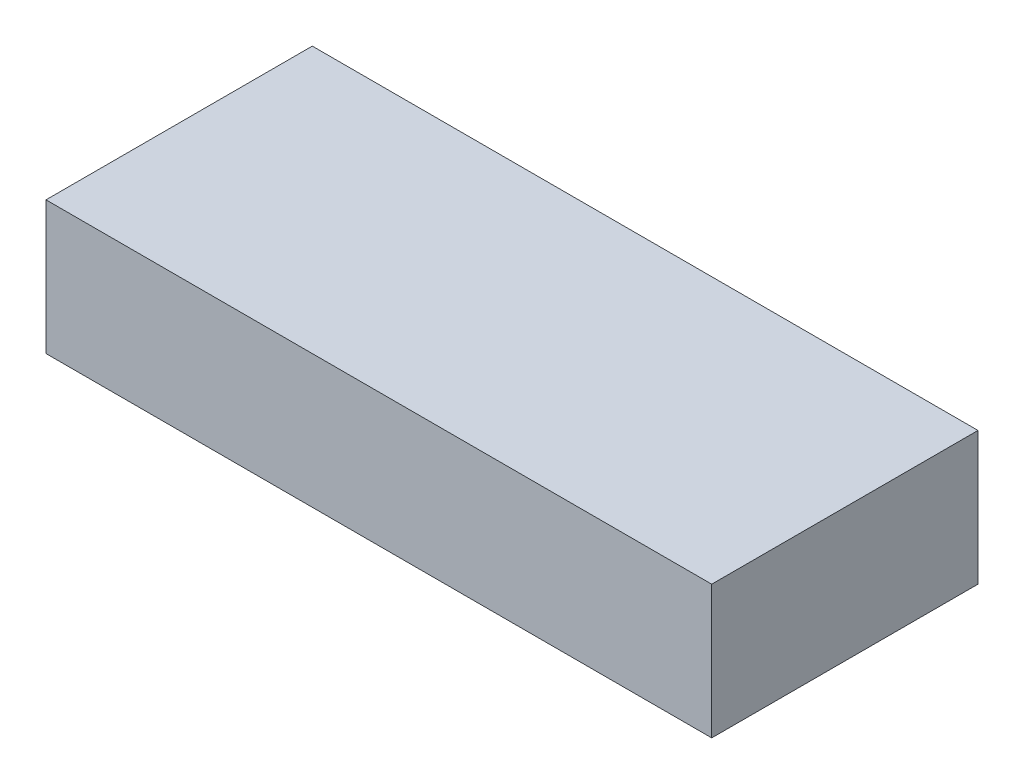
SolidWorks part; units mm, degrees
ref_plane "前视基准面" through (0, 0, 0) normal (0, 0, 1) x (1, 0, 0)
ref_plane "上视基准面" through (0, 0, 0) normal (0, 1, 0) x (1, 0, 0)
ref_plane "右视基准面" through (0, 0, 0) normal (1, 0, 0) x (0, 0, -1)
sketch "草图1" plane through (0, 0, 0) normal (0, 1, 0) x (1, 0, 0)
  line L1 (-500, -200) -> (500, -200)
  line L2 (-500, -200) -> (-500, 200)
  line L3 (-500, 200) -> (500, 200)
  line L4 (500, -200) -> (500, 200)
  line L5 (-500, -200) -> (500, 200) construction
  line L6 (-500, 200) -> (500, -200) construction
  point P0 (0, 0)
  dimension "D1" = 400
  dimension "D2" = 1000
extrude "凸台-拉伸1" add sketch "草图1" along normal blind 200
